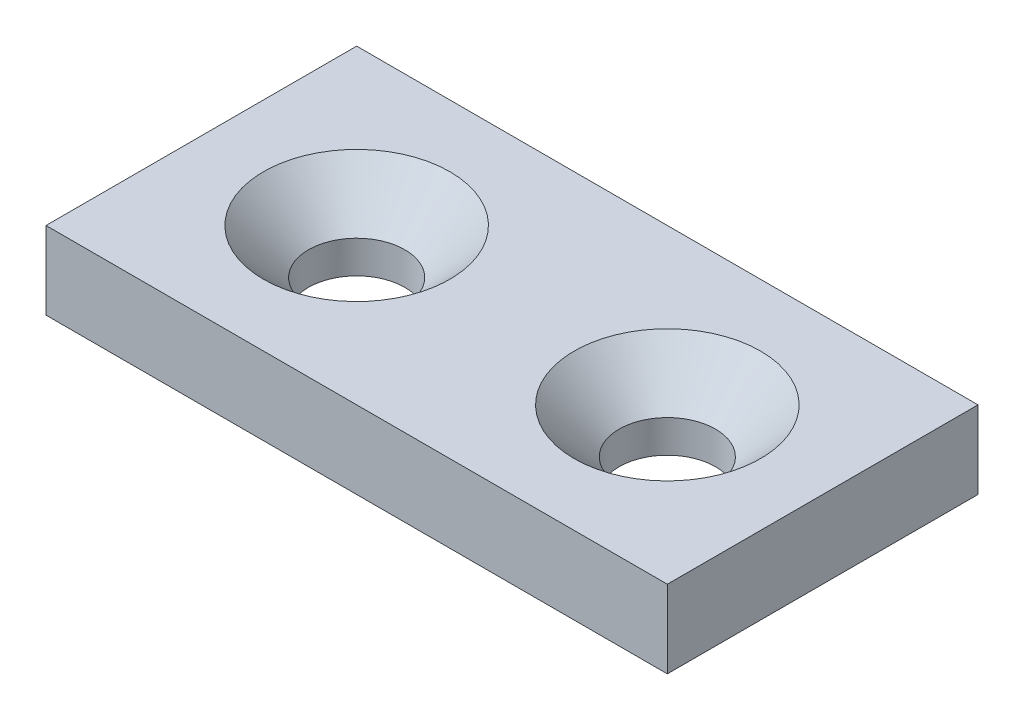
SolidWorks part; units mm, degrees
ref_plane "前视基准面" through (0, 0, 0) normal (0, 0, 1) x (1, 0, 0)
ref_plane "上视基准面" through (0, 0, 0) normal (0, 1, 0) x (1, 0, 0)
ref_plane "右视基准面" through (0, 0, 0) normal (1, 0, 0) x (0, 0, -1)
sketch "草图1" plane through (0, 0, 0) normal (0, 1, 0) x (1, 0, 0)
  line L1 (-20, -10) -> (20, -10)
  line L2 (-20, -10) -> (-20, 10)
  line L3 (-20, 10) -> (20, 10)
  line L4 (20, -10) -> (20, 10)
  line L5 (-20, -10) -> (20, 10) construction
  line L6 (-20, 10) -> (20, -10) construction
  point P0 (0, 0)
  dimension "D1" = 40
  dimension "D2" = 20
extrude "凸台-拉伸1" add sketch "草图1" along normal blind 5
hole_wizard "打孔尺寸(%根据)内六角花形半沉头螺钉的类型1" positions "草图2" profile "草图3" countersink size "M6" standard "GB" end condition up to next
sketch "草图2" plane through (0, 5, 0) normal (0, 1, 0) x (1, 0, 0)
  line L0 (0, -1000) -> (0, 49000) construction
  line L1 (-1000, 0) -> (49000, 0) construction
  point P0 (-10, 0)
  point P2 (10, 0)
  dimension "D1" = 20
sketch "草图3" plane through (-10, 5, 0) normal (1, 0, 0) x (0, 0, 1)
  line L0 (0, 0) -> (0, 5)
  line L1 (0, 5) -> (3.1, 5)
  line L2 (3.1, 5) -> (3.1, 2.9)
  line L3 (3.1, 2.9) -> (6, 0)
  line L5 (6, 0) -> (0, 0)
  line L6 (-3.1, 2.9) -> (-6, 0) construction
  line L11 (0, -6.35) -> (0, 107.95) construction
  dimension "通孔孔直径" = 6.2
  dimension "通孔孔深度" = 5
  dimension "近端锥形沉头孔直径" = 12
  dimension "近端锥形沉头孔角度" = 90
